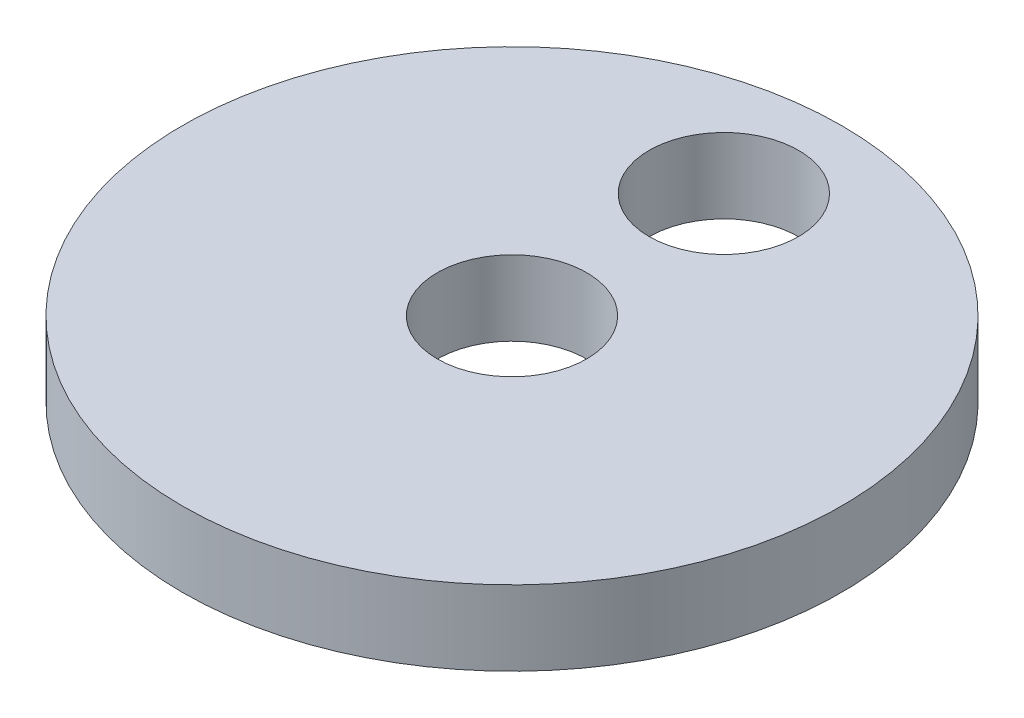
SolidWorks part; units mm, degrees
ref_plane "Front Plane" through (0, 0, 0) normal (0, 0, 1) x (1, 0, 0)
ref_plane "Top Plane" through (0, 0, 0) normal (0, 1, 0) x (1, 0, 0)
ref_plane "Right Plane" through (0, 0, 0) normal (1, 0, 0) x (0, 0, -1)
sketch "Sketch1" plane through (0, 0, 0) normal (0, 1, 0) x (1, 0, 0)
  circle A0 centre (0, 0) radius 14
  dimension "D1" = 28
extrude "Boss-Extrude1" add sketch "Sketch1" along normal blind 3.18
sketch "Sketch2" plane through (0, 3.18, 0) normal (0, 1, 0) x (1, 0, 0)
  circle A0 centre (0, 0) radius 3.175
  dimension "D1" = 6.35
extrude "Cut-Extrude1" cut sketch "Sketch2" against normal through all
sketch "Sketch3" plane through (0, 3.18, 0) normal (0, 1, 0) x (1, 0, 0)
  line L0 (0, 0) -> (0, 5.9797) construction
  circle A0 centre (0, 9) radius 3.175
  dimension "D1" = 6.35
  dimension "D2" = 9
extrude "Cut-Extrude2" cut sketch "Sketch3" against normal through all
